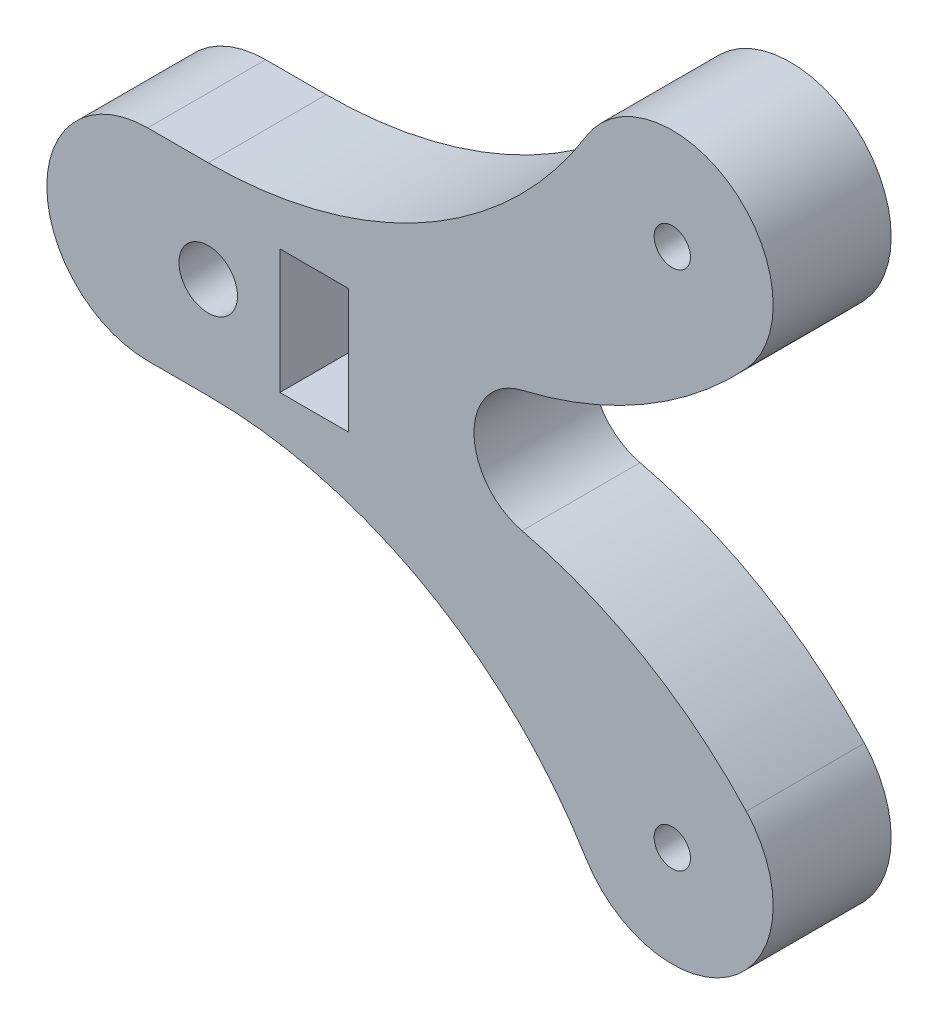
SolidWorks part; units mm, degrees
material "Acrylic (Medium-high impact)"
ref_plane "Front Plane" through (0, 0, 0) normal (0, 0, 1) x (1, 0, 0)
ref_plane "Top Plane" through (0, 0, 0) normal (0, 1, 0) x (1, 0, 0)
ref_plane "Right Plane" through (0, 0, 0) normal (1, 0, 0) x (0, 0, -1)
sketch "Sketch1" plane through (0, 0, 0) normal (0, 0, 1) x (1, 0, 0)
  line L0 (587.4699, 435.3658) -> (583.9197, 435.3658) construction
  line L1 (594.1695, 438.4483) -> (594.1695, 432.2833) construction
  line L2 (592.4695, 438.4483) -> (595.8695, 438.4483)
  line L3 (595.8695, 438.4483) -> (595.8695, 432.2833)
  line L4 (595.8695, 432.2833) -> (592.4695, 432.2833)
  line L5 (592.4695, 432.2833) -> (592.4695, 438.4483)
  line L6 (588.9197, 433.916) -> (588.9197, 430.3658) construction
  line L7 (588.9197, 436.8156) -> (588.9197, 440.3658) construction
  line L8 (592.4695, 435.3658) -> (595.8695, 435.3658) construction
  line L9 (588.9197, 440.3658) -> (585.9197, 440.3658)
  line L10 (611.9197, 448.2658) -> (611.9197, 422.4658) construction
  line L11 (611.9197, 422.4658) -> (611.9197, 425.7536) construction
  line L12 (602.0913, -564.4599) -> (602.0913, 49435.5401) construction
  line L13 (611.9197, 422.4658) -> (611.9197, 419.178) construction
  line L14 (588.9197, 430.3658) -> (585.9197, 430.3658)
  line L16 (611.9197, 448.2658) -> (611.9197, 451.5536) construction
  line L17 (611.9197, 448.2658) -> (611.9197, 444.978) construction
  line L20 (606.9306, 435.3658) -> (50606.9306, 435.3658) construction
  circle A0 centre (611.9197, 448.2658) radius 0.9
  circle A1 centre (611.9197, 422.4658) radius 0.9
  circle A2 centre (588.9197, 435.3658) radius 1.4498
  arc A3 (585.9197, 440.3658) -> (585.9197, 430.3658) centre (585.9197, 435.3658) ccw
  arc A4 (607.6499, 450.8675) -> (615.5881, 444.8684) centre (611.9197, 448.2658) cw
  arc A5 (588.9197, 440.3658) -> (607.6499, 450.8675) centre (588.9197, 462.3197) ccw
  arc A6 (604.4756, 438.3821) -> (604.4756, 432.3496) centre (605.1913, 435.3658) ccw
  arc A7 (604.4756, 438.3821) -> (615.5881, 444.8684) centre (599.3736, 459.8852) ccw
  arc A8 (604.4756, 432.3496) -> (615.5881, 425.8633) centre (599.3736, 410.8464) cw
  arc A9 (607.6499, 419.8641) -> (615.5881, 425.8633) centre (611.9197, 422.4658) ccw
  arc A10 (588.9197, 430.3658) -> (607.6499, 419.8641) centre (588.9197, 408.4119) cw
  point P33 (602.0913, 435.3658)
  point P35 (590.3695, 435.3658)
  dimension "D1" = 2.1
  dimension "D4" = 1.8
  dimension "D8" = 3.1
  dimension "D10" = 5
  dimension "D11" = 3
  dimension "D2" = 23
  dimension "D3" = 10
  dimension "D5" = 12.9
  dimension "D6" = 6.165
  dimension "D7" = 3.4
  dimension "D9" = 6.2218
  dimension "D12" = 18.7302
  dimension "D13" = 11.1125
extrude "Boss-Extrude1" add sketch "Sketch1" along normal blind 5.85
